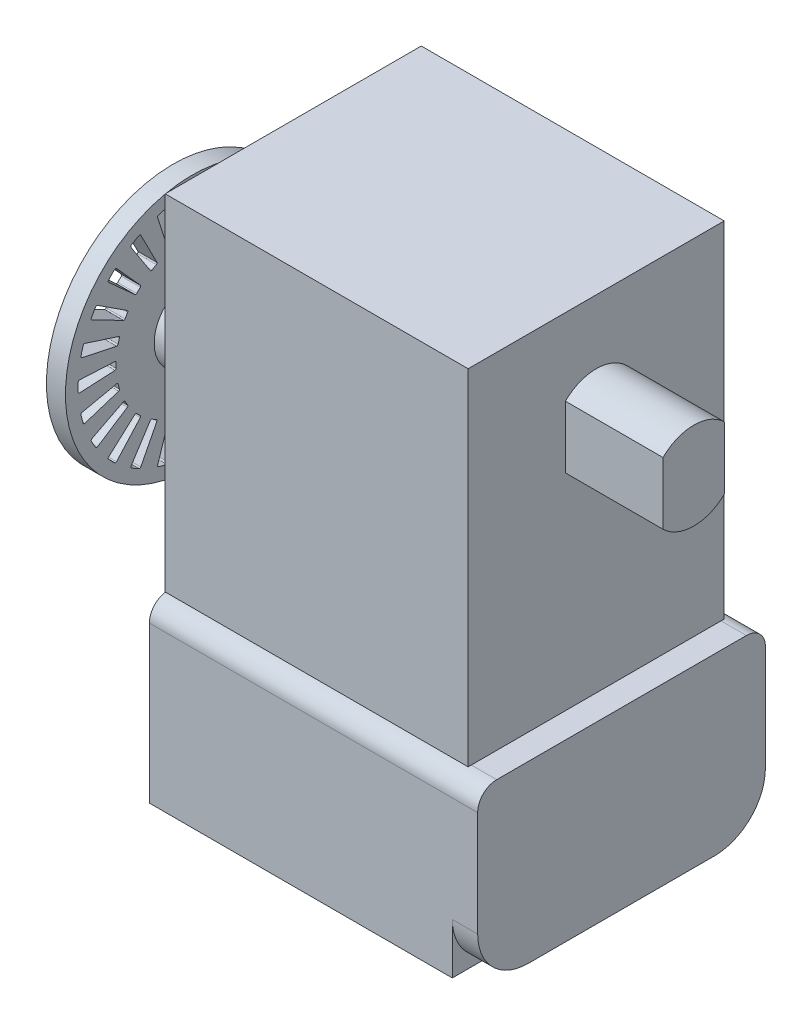
SolidWorks part; units mm, degrees
ref_plane "Plan de face" through (0, 0, 0) normal (0, 0, 1) x (1, 0, 0)
ref_plane "Plan de dessus" through (0, 0, 0) normal (0, 1, 0) x (1, 0, 0)
ref_plane "Plan de droite" through (0, 0, 0) normal (1, 0, 0) x (0, 0, -1)
sketch "Esquisse1" plane through (0, 0, 0) normal (0, 0, 1) x (1, 0, 0)
  line L1 (0, 0) -> (25.1, 0)
  line L2 (0, 0) -> (0, 27.2)
  line L3 (0, 27.2) -> (25.1, 27.2)
  line L4 (25.1, 0) -> (25.1, 27.2)
  dimension "D1" = 27.2
  dimension "D2" = 25.1
extrude "Extrusion1" add sketch "Esquisse1" along normal blind 20.2
sketch "Esquisse2" plane through (0, 0, 0) normal (-1, 0, 0) x (0, 0, 1)
  line L0 (20.2, 27.2) -> (0, 27.2) construction
  line L1 (0.25, 0) -> (19.95, 0)
  line L2 (-1.25, -1.5) -> (-1.25, -13.8)
  line L3 (-1.25, -13.8) -> (21.45, -13.8)
  line L4 (21.45, -1.5) -> (21.45, -13.8)
  line L5 (20.2, 0) -> (0, 0) construction
  line L6 (10.1, 27.2) -> (10.1, -17.3851) construction
  arc A0 (0.25, 0) -> (-1.25, -1.5) centre (0.25, -1.5) ccw
  arc A1 (19.95, 0) -> (21.45, -1.5) centre (19.95, -1.5) cw
  dimension "D3" = 1.5
  dimension "D4" = 1.5
  dimension "D1" = 41
  dimension "D2" = 22.7
extrude "Extrusion2" add sketch "Esquisse2" against normal up to surface (25.1 mm away) up to face at (25.1, 13.6, 10.1)
sketch "Esquisse9" plane through (0, 0, 21.45) normal (0, 0, 1) x (1, 0, 0)
  line L1 (0, -13.8) -> (1.2, -13.8)
  line L2 (0, -13.8) -> (0, 37.112)
  line L3 (0, 37.112) -> (1.2, 37.112)
  line L4 (1.2, -13.8) -> (1.2, 37.112)
  dimension "D1" = 1.2
extrude "Enlèv. mat.-Extru.2" cut sketch "Esquisse9" against normal through all
sketch "Esquisse4" plane through (25.1, 0, 0) normal (1, 0, 0) x (0, 0, -1)
  line L0 (1.25, -13.8) -> (1.25, -1.5) construction
  line L1 (-21.45, -1.5) -> (-21.45, -13.8) construction
  line L2 (1.25, -9.8) -> (1.25, -1.5)
  line L3 (-21.45, -1.5) -> (-21.45, -9.8)
  line L4 (-19.95, 0) -> (-0.25, 0)
  line L5 (-17.45, -13.8) -> (-2.75, -13.8)
  arc A0 (1.25, -1.5) -> (-0.25, 0) centre (-0.25, -1.5) ccw construction
  arc A1 (-19.95, 0) -> (-21.45, -1.5) centre (-19.95, -1.5) ccw construction
  arc A2 (1.25, -1.5) -> (-0.25, 0) centre (-0.25, -1.5) ccw
  arc A3 (-19.95, 0) -> (-21.45, -1.5) centre (-19.95, -1.5) ccw
  arc A4 (-21.45, -9.8) -> (-17.45, -13.8) centre (-17.45, -9.8) ccw
  arc A5 (1.25, -9.8) -> (-2.75, -13.8) centre (-2.75, -9.8) cw
  dimension "D1" = 4
extrude "Extrusion3" add sketch "Esquisse4" along normal blind 2
sketch "Esquisse5" plane through (25.1, 0, 0) normal (1, 0, 0) x (0, 0, -1)
  line L0 (-20.2, 27.2) -> (0, 27.2) construction
  line L1 (-20.2, 0) -> (-20.2, 27.2) construction
  line L4 (-12.529, 21.15) -> (-12.529, 16.25)
  line L6 (-7.671, 21.15) -> (-7.671, 16.25)
  arc A0 (-12.529, 16.25) -> (-7.671, 16.25) centre (-10.1, 18.7) ccw
  arc A1 (-7.671, 21.15) -> (-12.529, 21.15) centre (-10.1, 18.7) ccw
  dimension "D3" = 6.9
  dimension "D1" = 8.5
  dimension "D2" = 10.1
  dimension "D4" = 4.9
extrude "Extrusion4" add sketch "Esquisse5" along normal blind 7.7
sketch "Esquisse6" plane through (1.2, 0, 0) normal (-1, 0, 0) x (0, 0, 1)
  circle A0 centre (10.1, 9.45) radius 1.25
  dimension "D3" = 2.5
extrude "Extrusion5" add sketch "Esquisse6" along normal blind 10
ref_axis "Axe1" through (1.2, 9.45, 10.1) along (-1, 0, 0)
ref_plane "Plan2" through (0, 0, 10.1) normal (0, 0, 1) x (1, 0, 0)
sketch "Esquisse7" plane through (0, 0, 10.1) normal (0, 0, 1) x (1, 0, 0)
  line L0 (-8.27, 10.7) -> (-8.27, 19.45)
  line L1 (-8.27, 19.45) -> (-6.77, 19.45)
  line L2 (-6.77, 19.45) -> (-6.77, 12.45)
  line L3 (-6.77, 12.45) -> (-2.27, 12.45)
  line L4 (-2.27, 12.45) -> (-2.27, 10.7)
  line L5 (-2.27, 10.7) -> (-8.27, 10.7)
  line L7 (-8.8, 10.7) -> (-8.8, 8.2) construction
  line L8 (1.2, 9.45) -> (-8.8, 9.45) construction
  dimension "D1" = 0.53
  dimension "D2" = 1.5
  dimension "D3" = 6
  dimension "D4" = 3
  dimension "D5" = 10
revolve "Révolution1" add sketch "Esquisse7" angle 360 about axis through (1.2, 9.45, 10.1) along (-1, 0, 0)
sketch "Esquisse8" plane through (-8.27, 0, 0) normal (-1, 0, 0) x (0, 0, 1)
  line L0 (10.1, -22.55) -> (10.1, 22.55) construction
  line L1 (9.797, 15.5415) -> (9.6551, 18.3382)
  line L2 (10.403, 15.5415) -> (10.5449, 18.3382)
  line L3 (10.1, 9.45) -> (10.1, 20.9541) construction
  arc A0 (10.4489, 18.4432) -> (9.7511, 18.4432) centre (10.1, 9.45) ccw
  arc A1 (10.2998, 15.4467) -> (9.9002, 15.4467) centre (10.1, 9.45) ccw
  circle A2 centre (10.1, 9.45) radius 1.25 construction
  circle A3 centre (10.1, 9.45) radius 10 construction
  arc A4 (9.6551, 18.3382) -> (9.7511, 18.4432) centre (9.755, 18.3433) cw
  arc A5 (10.5449, 18.3382) -> (10.4489, 18.4432) centre (10.445, 18.3433) ccw
  arc A6 (10.403, 15.5415) -> (10.2998, 15.4467) centre (10.3031, 15.5466) cw
  arc A7 (9.797, 15.5415) -> (9.9002, 15.4467) centre (9.8969, 15.5466) ccw
  point P14 (9.65, 18.4387)
  point P17 (10.55, 18.4387)
  dimension "D2" = 3
  dimension "D3" = 1
  dimension "D4" = 0.1
  dimension "D1" = 0.9
extrude "Enlèv. mat.-Extru.1" cut sketch "Esquisse8" against normal up to next
pattern_circular "Répétition circulaire1" count 24 over 360 about axis through (0, 9.45, 10.1) along (1, 0, 0) of "Enlèv. mat.-Extru.1"
